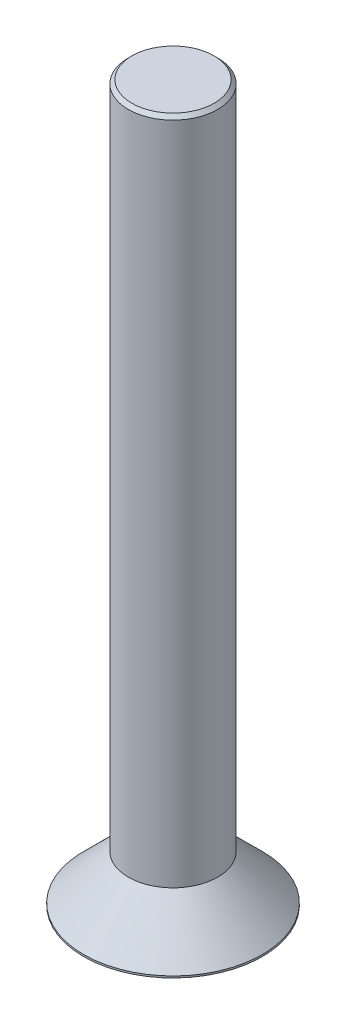
SolidWorks part; units mm, degrees
ref_plane "前视基准面" through (0, 0, 0) normal (0, 0, 1) x (1, 0, 0)
ref_plane "上视基准面" through (0, 0, 0) normal (0, 1, 0) x (1, 0, 0)
ref_plane "右视基准面" through (0, 0, 0) normal (1, 0, 0) x (0, 0, -1)
sketch "草图1" plane through (0, 0, 0) normal (0, 1, 0) x (1, 0, 0)
  circle A0 centre (0, 0) radius 5
  dimension "D1" = 10
extrude "凸台-拉伸1" add sketch "草图1" along normal blind 2.6
chamfer "倒角1" distance 2.5 angle 45 1 edges at (0, 2.6, 5)
sketch "草图2" plane through (0, 0, 0) normal (0, -1, 0) x (1, 0, 0)
  line L1 (1.54, -0.8891) -> (1.54, 0.8891)
  line L2 (1.54, 0.8891) -> (0, 1.7782)
  line L3 (0, 1.7782) -> (-1.54, 0.8891)
  line L4 (-1.54, 0.8891) -> (-1.54, -0.8891)
  line L5 (-1.54, -0.8891) -> (0, -1.7782)
  line L6 (0, -1.7782) -> (1.54, -0.8891)
  circle A0 centre (0, 0) radius 1.54 construction
  dimension "D1" = 3.08
extrude "切除-拉伸1" cut sketch "草图2" against normal blind 0.95
sketch "草图3" plane through (0, 2.6, 0) normal (0, 1, 0) x (1, 0, 0)
  circle A0 centre (0, 0) radius 2.5
  dimension "D1" = 5
extrude "凸台-拉伸2" add sketch "草图3" along normal blind 37.4
chamfer "倒角2" distance 0.2 angle 45 1 edges at (0, 40, 2.5)
